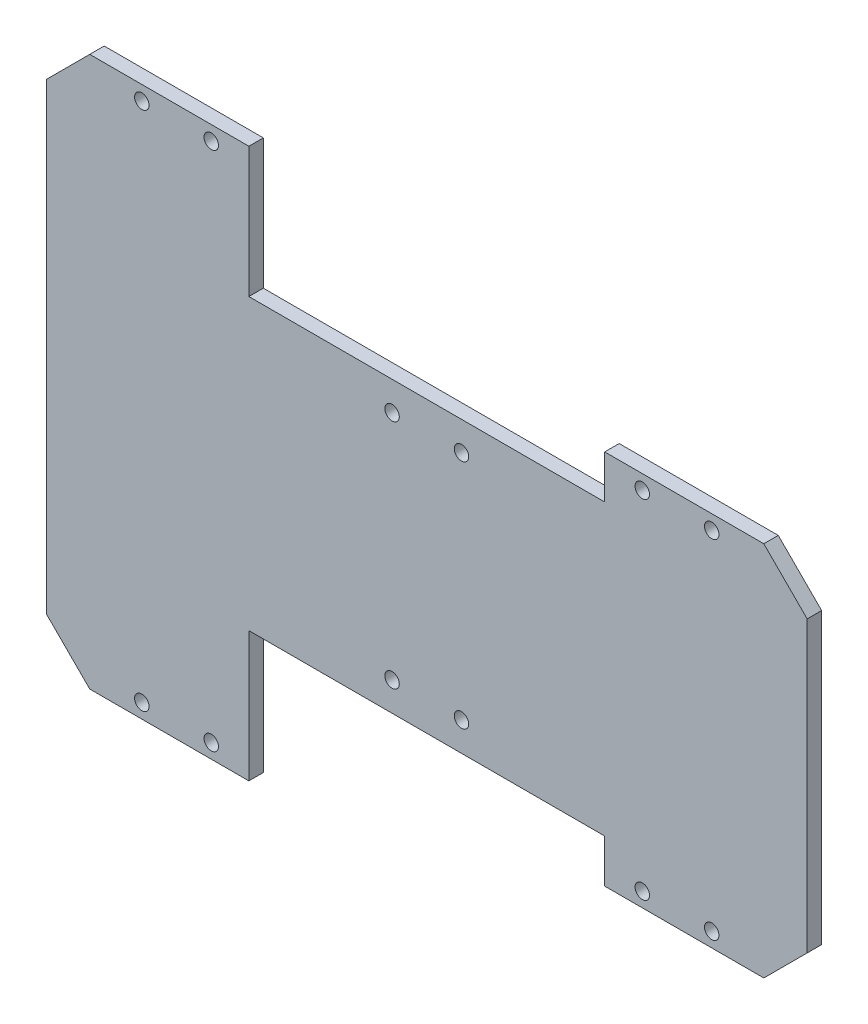
SolidWorks part; units mm, degrees
ref_plane "前视基准面" through (0, 0, 0) normal (0, 0, 1) x (1, 0, 0)
ref_plane "上视基准面" through (0, 0, 0) normal (0, 1, 0) x (1, 0, 0)
ref_plane "右视基准面" through (0, 0, 0) normal (1, 0, 0) x (0, 0, -1)
ref_plane "基准面4" through (0, 0, 5) normal (0, 0, 1) x (1, 0, 0)
sketch "草图1" plane through (0, 0, 5) normal (0, 0, 1) x (1, 0, 0)
  line L3 (50.93, -60) -> (50.93, 40)
  line L4 (50.93, 40) -> (35.93, 55)
  line L5 (35.93, 55) -> (-19.07, 55)
  line L6 (-19.07, 55) -> (-19.07, 40)
  line L7 (-19.07, 40) -> (-142.07, 40)
  line L8 (-142.07, 40) -> (-142.07, 85)
  line L9 (-142.07, 85) -> (-197.07, 85)
  line L10 (-197.07, 85) -> (-212.07, 70)
  line L11 (-212.07, 70) -> (-212.07, -90)
  line L44 (-197.07, -105) -> (-212.07, -90)
  line L45 (-142.07, -105) -> (-197.07, -105)
  line L46 (-142.07, -60) -> (-142.07, -105)
  line L47 (-19.07, -60) -> (-142.07, -60)
  line L48 (-19.07, -75) -> (-19.07, -60)
  line L49 (35.93, -75) -> (-19.07, -75)
  line L50 (50.93, -60) -> (35.93, -75)
  circle A0 centre (-179.07, 80) radius 2.5
  circle A3 centre (-6.07, 50) radius 2.5
  circle A6 centre (-155.07, 80) radius 2.5
  circle A8 centre (-92.57, 30) radius 2.5
  circle A9 centre (-68.57, 30) radius 2.5
  circle A10 centre (17.93, 50) radius 2.5
  circle A11 centre (17.93, -70) radius 2.5
  circle A12 centre (-68.57, -50) radius 2.5
  circle A13 centre (-92.57, -50) radius 2.5
  circle A14 centre (-155.07, -100) radius 2.5
  circle A15 centre (-6.07, -70) radius 2.5
  circle A16 centre (-179.07, -100) radius 2.5
  dimension "D3" = 33
  dimension "D4" = 5
  dimension "D5" = 45
  dimension "D7" = 24
  dimension "D8" = 5
  dimension "D9" = 5
  dimension "D10" = 5
  dimension "D11" = 5
  dimension "D12" = 24
  dimension "D13" = 5
  dimension "D6" = 24
  dimension "D19" = 15
  dimension "D22" = 5
  dimension "D20" = 13
  dimension "D16" = 33
  dimension "D2" = 135
  dimension "D14" = 135
  dimension "D17" = 13
  dimension "D18" = 123
  dimension "D21" = 15
  dimension "D26" = 15
extrude "凸台-拉伸1" add sketch "草图1" against normal blind 5
ref_plane "基准面5" through (-212.07, 70, 5) normal (0, -1, 0) x (-1, 0, 0)
